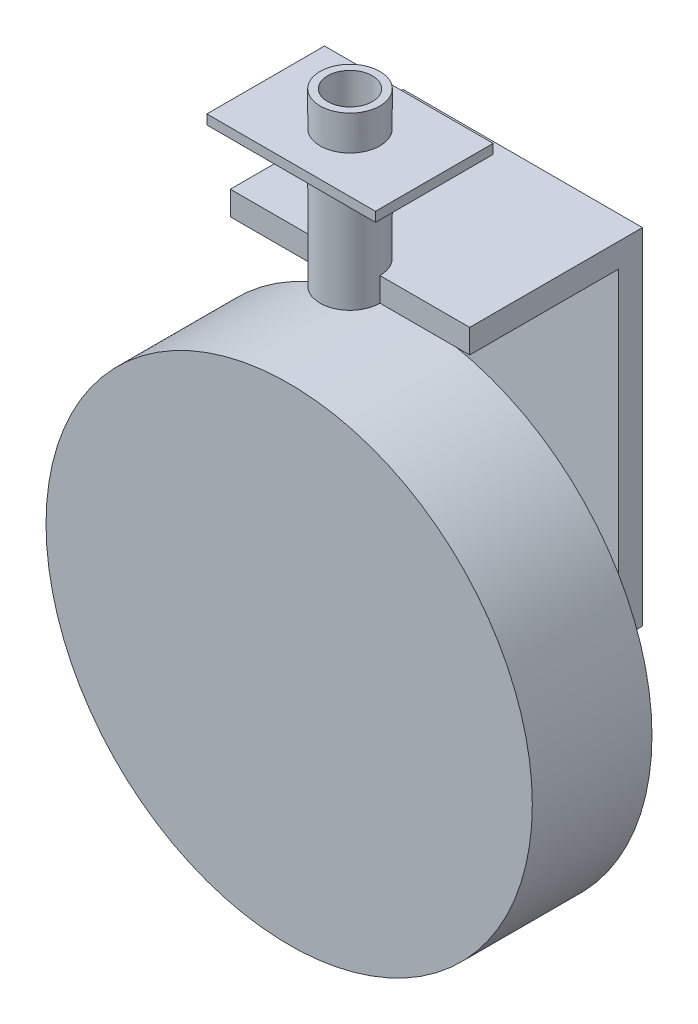
SolidWorks part; units mm, degrees
ref_plane "Front Plane" through (0, 0, 0) normal (0, 0, 1) x (1, 0, 0)
ref_plane "Top Plane" through (0, 0, 0) normal (0, 1, 0) x (1, 0, 0)
ref_plane "Right Plane" through (0, 0, 0) normal (1, 0, 0) x (0, 0, -1)
sketch "Sketch1" plane through (0, 0, 0) normal (0, 0, 1) x (1, 0, 0)
  circle A0 centre (0, 0) radius 101.6
extrude "Boss-Extrude1" add sketch "Sketch1" along normal blind 50
sketch "Sketch3" plane through (0, 0, 0) normal (1, 0, 0) x (0, 0, -1)
  line L0 (-24.5796, 0) -> (37.6371, 0)
  line L1 (37.6371, 0) -> (37.6371, 124.2182)
  line L2 (37.6371, 124.2182) -> (-24.5796, 124.2182)
  line L4 (-24.5796, 0) -> (-24.5796, 124.2182) construction
  point P4 (-24.5796, 121.3125)
sketch "Sketch4" plane through (0, 0, 0) normal (1, 0, 0) x (0, 0, -1)
  line L0 (-24.5796, 124.2182) -> (-24.5796, 195.5897)
revolve "Revolve-Thin1" add sketch "Sketch4" angle 360 about L0 wall 12.5
extrude "Extrude-Thin1" add sketch "Sketch3" along normal blind 50 and the other way blind 50 thin
sketch "Sketch5" plane through (0, 195.5897, 0) normal (0, 1, 0) x (1, 0, 0)
  circle A0 centre (0, -24.5796) radius 9.3661
extrude "Cut-Extrude1" cut sketch "Sketch5" against normal blind 50
ref_plane "Plane1" through (0, 177.1262, 0) normal (0, 1, 0) x (1, 0, 0)
sketch "Sketch6" plane through (0, 177.1262, 0) normal (0, 1, 0) x (1, 0, 0)
  line L1 (35.2328, -49.1592) -> (-35.2328, -49.1592)
  line L2 (35.2328, -49.1592) -> (35.2328, 0)
  line L3 (35.2328, 0) -> (-35.2328, 0)
  line L4 (-35.2328, -49.1592) -> (-35.2328, 0)
  line L5 (35.2328, -49.1592) -> (-35.2328, 0) construction
  line L6 (35.2328, 0) -> (-35.2328, -49.1592) construction
  point P0 (0, -24.5796)
extrude "Boss-Extrude2" add sketch "Sketch6" along normal blind 4
